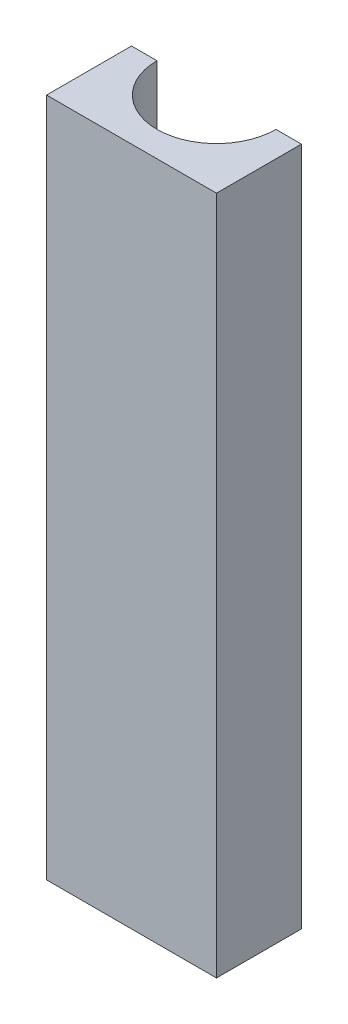
SolidWorks part; units mm, degrees
ref_plane "Piano frontale" through (0, 0, 0) normal (0, 0, 1) x (1, 0, 0)
ref_plane "Piano superiore" through (0, 0, 0) normal (0, 1, 0) x (1, 0, 0)
ref_plane "Piano destro" through (0, 0, 0) normal (1, 0, 0) x (0, 0, -1)
sketch "Schizzo1" plane through (0, 0, 0) normal (0, 1, 0) x (1, 0, 0)
  line L1 (0, 0) -> (20, 0)
  line L2 (0, 0) -> (0, 10)
  line L3 (0, 10) -> (20, 10)
  line L4 (20, 0) -> (20, 10)
  dimension "D1" = 20
  dimension "D2" = 10
extrude "Estrusione-Estrusione1" add sketch "Schizzo1" along normal blind 80
sketch "Schizzo3" plane through (0, 80, 0) normal (0, 1, 0) x (1, 0, 0)
  line L0 (20, 10) -> (0, 10) construction
  circle A0 centre (10, 10) radius 7
extrude "Taglio-Estrusione1" cut sketch "Schizzo3" against normal through all contours A0
